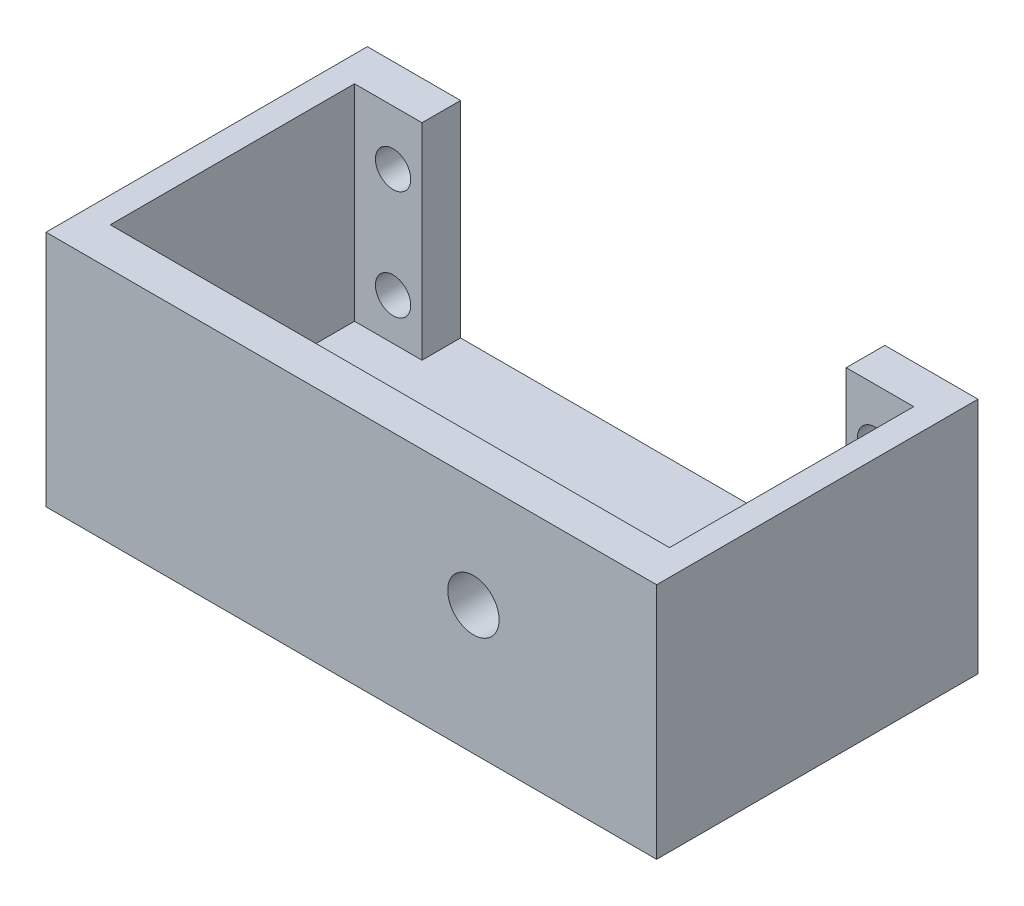
SolidWorks part; units mm, degrees
material "ABS"
ref_plane "Front Plane" through (0, 0, 0) normal (0, 0, 1) x (1, 0, 0)
ref_plane "Top Plane" through (0, 0, 0) normal (0, 1, 0) x (1, 0, 0)
ref_plane "Right Plane" through (0, 0, 0) normal (1, 0, 0) x (0, 0, -1)
sketch "Sketch1" plane through (0, 0, 0) normal (0, 1, 0) x (1, 0, 0)
  line L1 (-47.5, 25) -> (47.5, 25)
  line L2 (-47.5, 25) -> (-47.5, -25)
  line L3 (-47.5, -25) -> (47.5, -25)
  line L4 (47.5, 25) -> (47.5, -25)
  line L5 (-47.5, 25) -> (47.5, -25) construction
  line L6 (-47.5, -25) -> (47.5, 25) construction
  point P0 (0, 0)
  dimension "D1" = 95
  dimension "D2" = 50
extrude "Boss-Extrude1" add sketch "Sketch1" along normal blind 5
sketch "Sketch2" plane through (0, 5, 0) normal (0, 1, 0) x (1, 0, 0)
  line L0 (0, 25) -> (0, -25) construction
  line L1 (-47.5, -25) -> (47.5, -25) construction
  line L2 (-33, 25) -> (-33, -25) construction
  line L3 (47.5, 25) -> (-47.5, 25) construction
  line L4 (-47.5, 25) -> (-47.5, -25) construction
  line L5 (-33, 25) -> (-47.5, 25)
  line L6 (-33, 25) -> (-33, 19)
  line L7 (-33, 19) -> (-47.5, 19)
  line L8 (-47.5, 25) -> (-47.5, 19)
  line L9 (33, 19) -> (47.5, 19)
  line L10 (47.5, 25) -> (47.5, 19)
  line L11 (33, 25) -> (47.5, 25)
  line L12 (33, 25) -> (33, 19)
  point P6 (0, 0)
  dimension "D1" = 33
  dimension "D2" = 6
extrude "Boss-Extrude2" add sketch "Sketch2" along normal blind 32
sketch "Sketch3" plane through (0, 37, 0) normal (0, 1, 0) x (1, 0, 0)
  line L1 (-47.5, 25) -> (47.5, 25)
  line L2 (-47.5, 25) -> (-47.5, 19)
  line L3 (-47.5, 19) -> (47.5, 19)
  line L4 (47.5, 25) -> (47.5, 19)
extrude "Boss-Extrude3" [suppressed] add sketch "Sketch3" against normal blind 6
sketch "Sketch4" plane through (0, 0, -25) normal (0, 0, -1) x (-1, 0, 0)
  line L0 (0, 0) -> (0, 43) construction
  line L2 (-33, 5) -> (33, 5) construction
  circle A0 centre (37.5, 11.5) radius 2.75
  circle A1 centre (37.5, 28.5) radius 2.75
  circle A2 centre (-37.5, 28.5) radius 2.75
  circle A3 centre (-37.5, 11.5) radius 2.75
  dimension "D1" = 5.5
  dimension "D4" = 5.5
  dimension "D2" = 37.5
  dimension "D3" = 17
extrude "Cut-Extrude1" cut sketch "Sketch4" against normal blind 6
sketch "Sketch6" plane through (0, 5, 0) normal (0, 1, 0) x (1, 0, 0)
  line L0 (-47.5, -25) -> (47.5, -25) construction
  line L2 (0, 0) -> (0, -25) construction
  circle A0 centre (-38, 0) radius 2.7
  circle A1 centre (38, 0) radius 2.7
  dimension "D1" = 25
  dimension "D2" = 76
extrude "Cut-Extrude2" cut sketch "Sketch6" against normal blind 6
sketch "Sketch7" plane through (-47.5, 0, 0) normal (-1, 0, 0) x (0, 0, 1)
  line L0 (25, 5) -> (-19, 37)
  line L1 (-19, 37) -> (-19, 5)
  line L2 (-19, 5) -> (25, 5)
extrude "Boss-Extrude4" [suppressed] add sketch "Sketch7" against normal blind 4
mirror "Mirror1" [suppressed] about plane through (0, 0, 0) normal (1, 0, 0)
sketch "Sketch9" [suppressed] plane through (0, 5, 0) normal (0, 1, 0) x (1, 0, 0)
  line L0 (47.5, -20) -> (47.5, 14) construction
  line L1 (-47.5, -20) -> (47.5, -20)
  line L2 (-47.5, -20) -> (-47.5, -14)
  line L3 (-47.5, -14) -> (47.5, -14)
  line L4 (47.5, -20) -> (47.5, -14)
  dimension "D1" = 6
sketch "Sketch10" plane through (0, 5, 0) normal (0, 1, 0) x (1, 0, 0)
  line L0 (47.5, -25) -> (47.5, 19) construction
  line L1 (-47.5, -25) -> (47.5, -25)
  line L2 (-47.5, -25) -> (-47.5, -14)
  line L3 (-43.5, -19) -> (43.5, -19)
  line L4 (47.5, -25) -> (47.5, -19)
  line L5 (-47.5, 19) -> (-33, 19) construction
  line L6 (-47.5, -25) -> (-43.5, -25)
  line L7 (-47.5, -25) -> (-47.5, 19)
  line L8 (-47.5, 19) -> (-43.5, 19)
  line L9 (-43.5, -19) -> (-43.5, 19)
  line L10 (33, 19) -> (47.5, 19) construction
  line L11 (47.5, -25) -> (43.5, -25)
  line L12 (47.5, -25) -> (47.5, 19)
  line L13 (47.5, 19) -> (43.5, 19)
  line L14 (43.5, -19) -> (43.5, 19)
  line M12 (47.5, 19) -> (33, 19)
  line M16 (-33, 19) -> (-47.5, 19)
  line M17 (-47.5, 19) -> (-47.5, -25)
  line M18 (-47.5, -25) -> (47.5, -25)
  line M19 (47.5, -25) -> (47.5, 19)
  dimension "D1" = 6
  dimension "D2" = 4
  dimension "D3" = 4
extrude "Boss-Extrude5" add sketch "Sketch10" along normal blind 32 contours L14 L3 L9 L1 M16 M17 M18 M19 M12
sketch "Sketch11" plane through (0, 0, 25) normal (0, 0, 1) x (1, 0, 0)
  circle A0 centre (19, 20) radius 4
extrude "Cut-Extrude3" cut sketch "Sketch11" against normal blind 6
